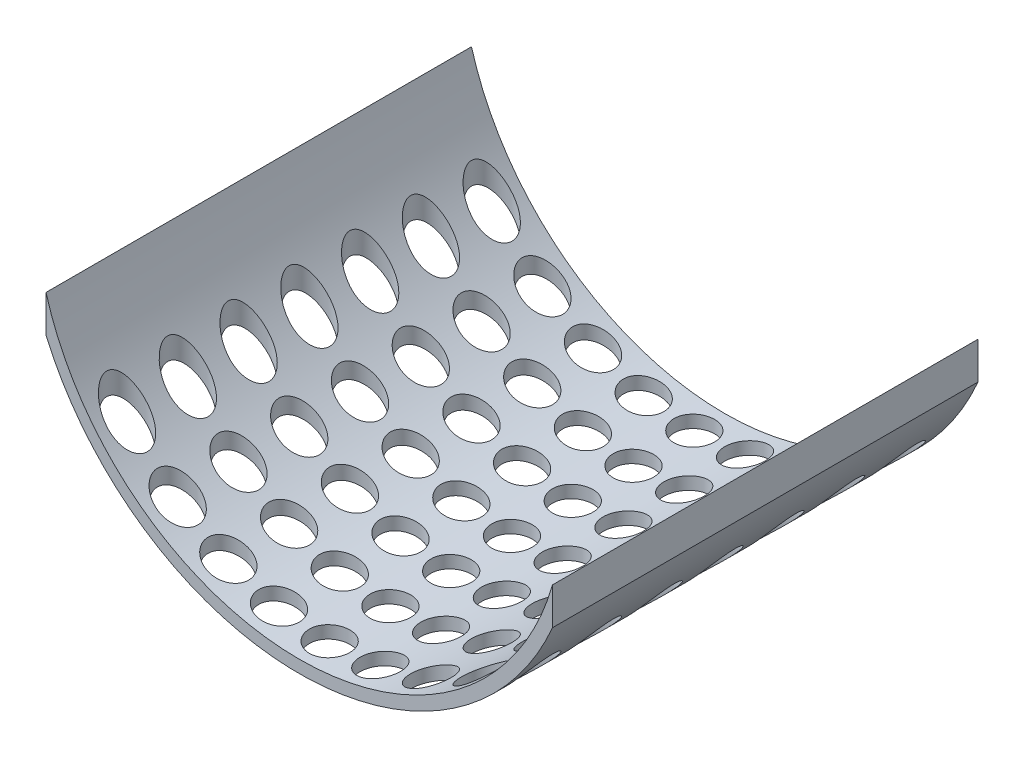
SolidWorks part; units mm, degrees
ref_plane "Front Plane" through (0, 0, 0) normal (0, 0, 1) x (1, 0, 0)
ref_plane "Top Plane" through (0, 0, 0) normal (0, 1, 0) x (1, 0, 0)
ref_plane "Right Plane" through (0, 0, 0) normal (1, 0, 0) x (0, 0, -1)
sketch "Sketch1" plane through (0, 0, 0) normal (0, 0, 1) x (1, 0, 0)
  line L0 (-139.9413, 0) -> (139.9413, 0) construction
  line L1 (0, -91.1929) -> (0, 91.1929) construction
  line L2 (-125, -95.7162) -> (-125, 95.7162) construction
  line L3 (125, -95.7162) -> (125, 95.7162) construction
  line L4 (-125, -35.7071) -> (-125, -54.0244)
  line L5 (125, -35.7071) -> (125, -54.0244)
  arc A0 (-125, -35.7071) -> (125, -35.7071) centre (0, 0) ccw
  arc A1 (-125, -54.0244) -> (125, -54.0244) centre (0, 0) ccw
  arc A3 (-130, 0) -> (130, 0) centre (0, 0) ccw construction
  arc A4 (-136.175, 0) -> (136.175, 0) centre (0, 0) ccw construction
  point P4 (0, 0)
  point P8 (0, 0)
  point P17 (-125, 0)
  dimension "D1" = 130
  dimension "D3" = 125
  dimension "D2" = 6.175
extrude "Boss-Extrude1" add sketch "Sketch1" along normal mid plane 210
sketch "Sketch2" plane through (0, 0, 0) normal (0, 1, 0) x (1, 0, 0)
  line L0 (-265.4313, 0) -> (265.4313, 0) construction
  line L1 (0, -153.3443) -> (0, 153.3443) construction
  circle A0 centre (0, 0) radius 10
  circle A1 centre (25, 0) radius 10
  circle A2 centre (50, 0) radius 10
  circle A3 centre (75, 0) radius 10
  circle A4 centre (100, 0) radius 10
  circle A5 centre (25, 30) radius 10
  circle A6 centre (50, 30) radius 10
  circle A7 centre (75, 30) radius 10
  circle A8 centre (100, 30) radius 10
  circle A9 centre (25, 60) radius 10
  circle A10 centre (50, 60) radius 10
  circle A11 centre (75, 60) radius 10
  circle A12 centre (100, 60) radius 10
  circle A13 centre (25, 90) radius 10
  circle A14 centre (50, 90) radius 10
  circle A15 centre (75, 90) radius 10
  circle A16 centre (100, 90) radius 10
  circle A17 centre (0, 30) radius 10
  circle A18 centre (0, 60) radius 10
  circle A19 centre (0, 90) radius 10
  circle A20 centre (0, -90) radius 10
  circle A21 centre (0, -60) radius 10
  circle A22 centre (0, -30) radius 10
  circle A23 centre (100, -90) radius 10
  circle A24 centre (75, -90) radius 10
  circle A25 centre (50, -90) radius 10
  circle A26 centre (25, -90) radius 10
  circle A27 centre (100, -60) radius 10
  circle A28 centre (75, -60) radius 10
  circle A29 centre (50, -60) radius 10
  circle A30 centre (25, -60) radius 10
  circle A31 centre (100, -30) radius 10
  circle A32 centre (75, -30) radius 10
  circle A33 centre (50, -30) radius 10
  circle A34 centre (25, -30) radius 10
  circle A35 centre (-25, -30) radius 10
  circle A36 centre (-50, -30) radius 10
  circle A37 centre (-75, -30) radius 10
  circle A38 centre (-100, -30) radius 10
  circle A39 centre (-25, -60) radius 10
  circle A40 centre (-50, -60) radius 10
  circle A41 centre (-75, -60) radius 10
  circle A42 centre (-100, -60) radius 10
  circle A43 centre (-25, -90) radius 10
  circle A44 centre (-50, -90) radius 10
  circle A45 centre (-75, -90) radius 10
  circle A46 centre (-100, -90) radius 10
  circle A47 centre (-100, 90) radius 10
  circle A48 centre (-75, 90) radius 10
  circle A49 centre (-50, 90) radius 10
  circle A50 centre (-25, 90) radius 10
  circle A51 centre (-100, 60) radius 10
  circle A52 centre (-75, 60) radius 10
  circle A53 centre (-50, 60) radius 10
  circle A54 centre (-25, 60) radius 10
  circle A55 centre (-100, 30) radius 10
  circle A56 centre (-75, 30) radius 10
  circle A57 centre (-50, 30) radius 10
  circle A58 centre (-25, 30) radius 10
  circle A59 centre (-100, 0) radius 10
  circle A60 centre (-75, 0) radius 10
  circle A61 centre (-50, 0) radius 10
  circle A62 centre (-25, 0) radius 10
  point P4 (0, 0)
  point P8 (0, 0)
  dimension "D1" = 20
  dimension "D2" = 5
  dimension "D3" = 4
extrude "Cut-Extrude1" cut sketch "Sketch2" against normal blind 200
